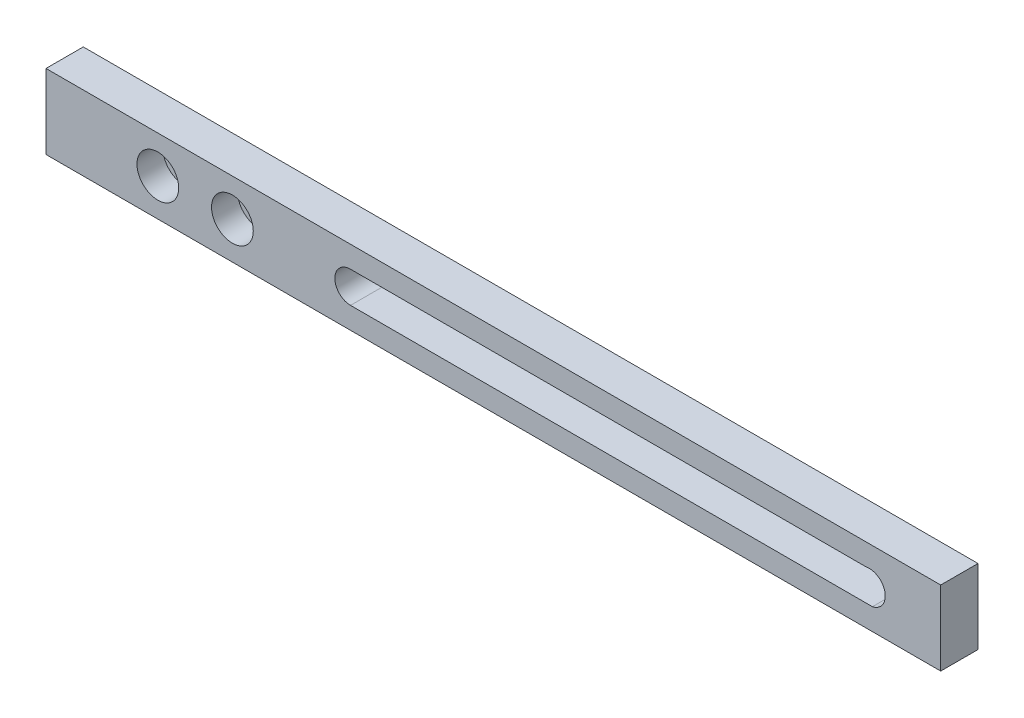
SolidWorks part; units mm, degrees
material "6061 Сплав"
ref_plane "Front" through (0, 0, 0) normal (0, 0, 1) x (1, 0, 0)
ref_plane "Top" through (0, 0, 0) normal (0, 1, 0) x (1, 0, 0)
ref_plane "Right" through (0, 0, 0) normal (1, 0, 0) x (0, 0, -1)
sketch "Эскиз1" plane through (0, 0, 0) normal (0, 0, 1) x (1, 0, 0)
  line L1 (-60, 5) -> (60, 5)
  line L2 (-60, 5) -> (-60, -5)
  line L3 (-60, -5) -> (60, -5)
  line L4 (60, 5) -> (60, -5)
  line L5 (-60, 5) -> (60, -5) construction
  line L6 (-60, -5) -> (60, 5) construction
  point P0 (0, 0)
  dimension "D1" = 120
  dimension "D2" = 10
extrude "Бобышка-Вытянуть1" add sketch "Эскиз1" along normal blind 5
sketch "Эскиз2" plane through (0, 0, 5) normal (0, 0, 1) x (1, 0, 0)
  line L0 (60, 5) -> (-60, 5) construction
  line L1 (-19.1604, 2.1) -> (50, 2.1)
  line L2 (-60, 5) -> (-60, -5) construction
  line L3 (-19.1604, -2.1) -> (50.8396, -2.1)
  line L4 (60, -5) -> (60, 5) construction
  line L5 (-19.1604, 2.1) -> (50.8396, -2.1) construction
  line L6 (-19.1604, -2.1) -> (50, 2.1) construction
  arc A0 (50, 2.1) -> (50.8396, -2.1) centre (50.4198, 0) cw
  arc A1 (-19.1604, 2.1) -> (-19.1604, -2.1) centre (-19.1604, 0) ccw
  circle A2 centre (-45, 0) radius 1.25
  circle A3 centre (-35, 0) radius 1.25
  point P0 (15.6285, 0.0127)
  point P13 (-60, 0)
  dimension "D4" = 10
  dimension "D1" = 70
  dimension "D2" = 4.2
  dimension "D3" = 2.9
  dimension "D5" = 15
  dimension "D6" = 5
  dimension "D7" = 10
extrude "Вырез-Вытянуть1" cut sketch "Эскиз2" against normal blind 5
sketch "Эскиз3" plane through (0, 0, 5) normal (0, 0, 1) x (1, 0, 0)
  circle A0 centre (-45, 0) radius 2.8
  circle A1 centre (-35, 0) radius 2.8
extrude "Вырез-Вытянуть2" cut sketch "Эскиз3" against normal blind 3.5
